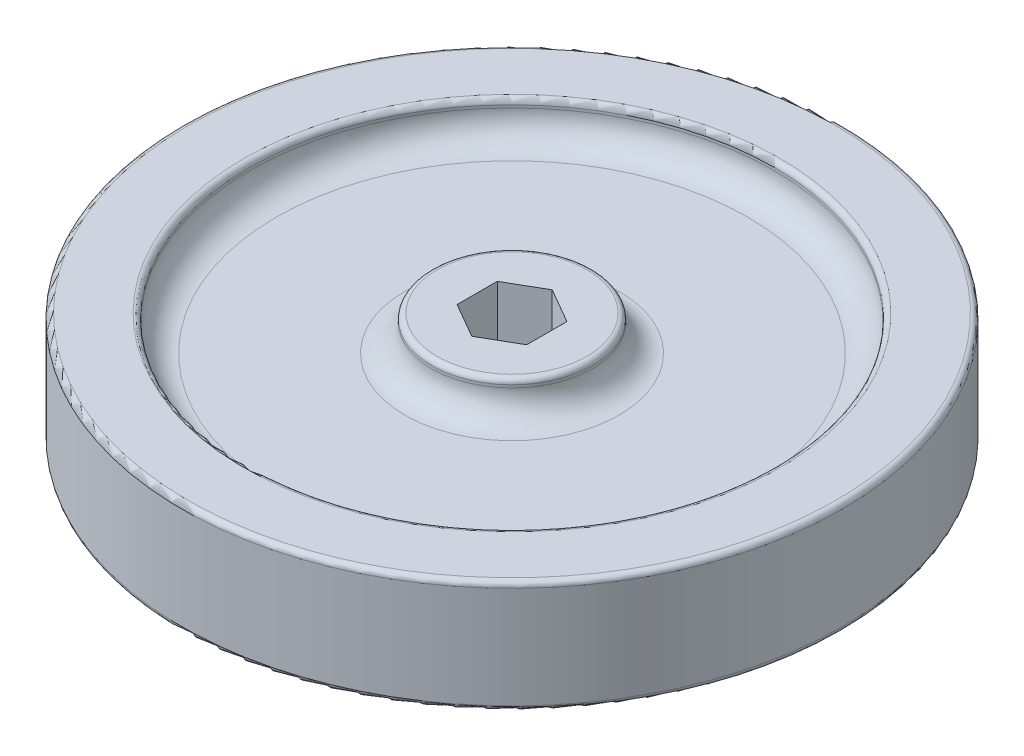
SolidWorks part; units mm, degrees
ref_plane "Front Plane" through (0, 0, 0) normal (0, 0, 1) x (1, 0, 0)
ref_plane "Top Plane" through (0, 0, 0) normal (0, 1, 0) x (1, 0, 0)
ref_plane "Right Plane" through (0, 0, 0) normal (1, 0, 0) x (0, 0, -1)
sketch "Sketch1" plane through (0, 0, 0) normal (0, 0, 1) x (1, 0, 0)
  line L0 (0, -554.9311) -> (0, 27191.6255) construction
  line L1 (0, 0) -> (15, 0)
  line L2 (15, 0) -> (15, 6.5)
  line L3 (15, 6.5) -> (49, 6.5)
  line L4 (49, 6.5) -> (49, 0)
  line L5 (49, 0) -> (61.5, 0)
  line L6 (61.5, 0) -> (61.5, 21)
  line L7 (61.5, 21) -> (49, 21)
  line L8 (49, 21) -> (49, 14.5)
  line L9 (49, 14.5) -> (15, 14.5)
  line L10 (15, 14.5) -> (15, 21)
  line L11 (15, 21) -> (0, 21)
  line L12 (0, 21) -> (0, 0)
  dimension "D1" = 15
  dimension "D2" = 61.5
  dimension "D3" = 12.5
  dimension "D4" = 6.5
  dimension "D5" = 21
revolve "Revolve1" add sketch "Sketch1" angle 360 about L0
sketch "Sketch2" plane through (0, 21, 0) normal (0, 1, 0) x (1, 0, 0)
  line L1 (0, 7.5056) -> (-6.5, 3.7528)
  line L2 (-6.5, 3.7528) -> (-6.5, -3.7528)
  line L3 (-6.5, -3.7528) -> (0, -7.5056)
  line L4 (0, -7.5056) -> (6.5, -3.7528)
  line L5 (6.5, -3.7528) -> (6.5, 3.7528)
  line L6 (6.5, 3.7528) -> (0, 7.5056)
  circle A0 centre (0, 0) radius 6.5 construction
  dimension "D1" = 13
extrude "Cut-Extrude1" cut sketch "Sketch2" against normal through all
fillet "Fillet1" radius 1 6 edges at (15, 0, 0) (15, 21, 0) (49, 21, 0) (49, 0, 0) (61.5, 0, 0) (61.5, 21, 0)
fillet "Fillet2" radius 5 4 edges at (49, 6.5, 0) (15, 6.5, 0) (49, 14.5, 0) (15, 14.5, 0)
